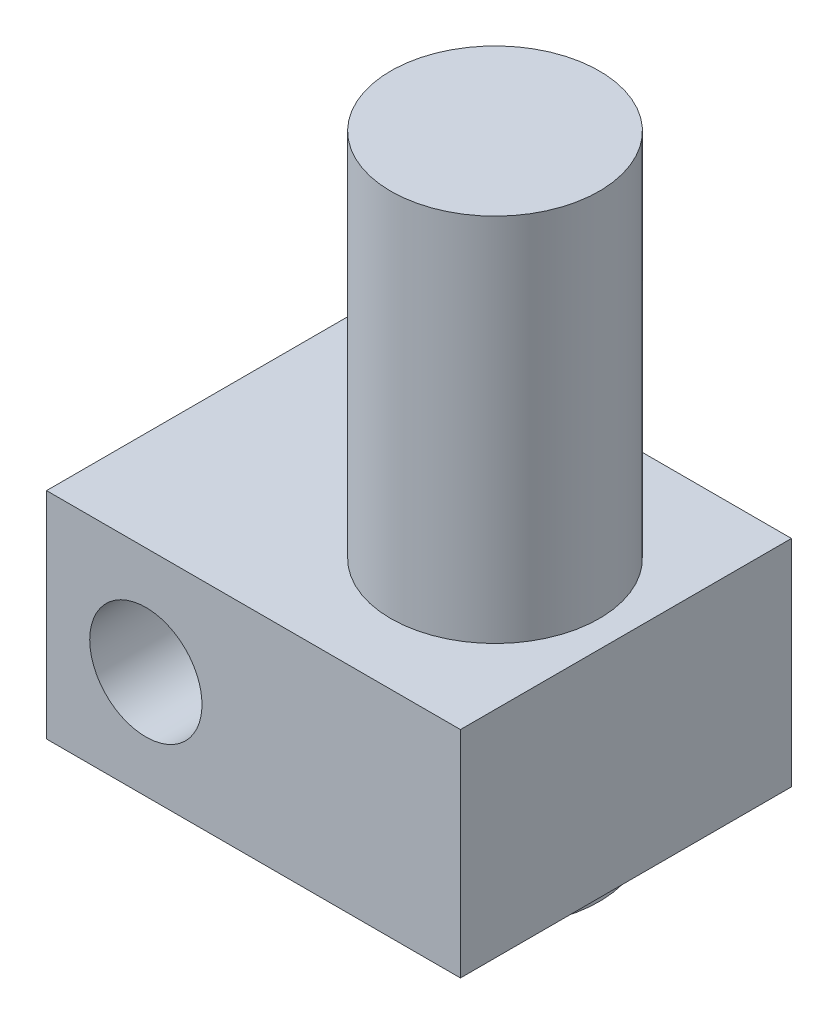
SolidWorks part; units mm, degrees
ref_plane "Front Plane" through (0, 0, 0) normal (0, 0, 1) x (1, 0, 0)
ref_plane "Top Plane" through (0, 0, 0) normal (0, 1, 0) x (1, 0, 0)
ref_plane "Right Plane" through (0, 0, 0) normal (1, 0, 0) x (0, 0, -1)
sketch "Sketch1" plane through (0, 0, 0) normal (0, 1, 0) x (1, 0, 0)
  line L1 (-7.94, 6.35) -> (7.94, 6.35)
  line L2 (-7.94, 6.35) -> (-7.94, -6.35)
  line L3 (-7.94, -6.35) -> (7.94, -6.35)
  line L4 (7.94, 6.35) -> (7.94, -6.35)
  line L5 (-7.94, 6.35) -> (7.94, -6.35) construction
  line L6 (-7.94, -6.35) -> (7.94, 6.35) construction
  point P0 (0, 0)
  dimension "D1" = 12.7
  dimension "D2" = 15.88
extrude "Boss-Extrude1" add sketch "Sketch1" along normal blind 8.255
sketch "Sketch2" plane through (0, 8.255, 0) normal (0, 1, 0) x (1, 0, 0)
  line L0 (7.94, 0) -> (2.917, 0) construction
  line L1 (7.94, -6.35) -> (7.94, 6.35) construction
  line L2 (2.917, 0) -> (2.917, 6.35) construction
  line L3 (7.94, 6.35) -> (-7.94, 6.35) construction
  circle A0 centre (2.917, 0) radius 4
  dimension "D2" = 8
  dimension "D1" = 5.023
extrude "Boss-Extrude2" add sketch "Sketch2" along normal blind 14.2 and the other way blind 11 contours A0
chamfer "Chamfer1" distance 3 angle 28 1 edges at (2.917, -2.745, 4)
sketch "Sketch4" plane through (0, -2.745, 0) normal (0, -1, 0) x (1, 0, 0)
  circle A1 centre (2.917, 0) radius 1
  circle A2 centre (2.917, 0) radius 1
  dimension "D1" = 0
extrude "Boss-Extrude3" add sketch "Sketch4" along normal blind 0.5
sketch "Sketch5" plane through (0, 0, -6.35) normal (0, 0, -1) x (-1, 0, 0)
  line L0 (7.94, 4.1275) -> (4.13, 4.1275) construction
  line L1 (7.94, 8.255) -> (7.94, 0) construction
  line L2 (4.13, 4.1275) -> (4.13, 0) construction
  line L3 (-7.94, 0) -> (7.94, 0) construction
  circle A0 centre (4.13, 4.1275) radius 2.1534
  dimension "D1" = 3.81
extrude "Cut-Extrude1" cut sketch "Sketch5" against normal through all
